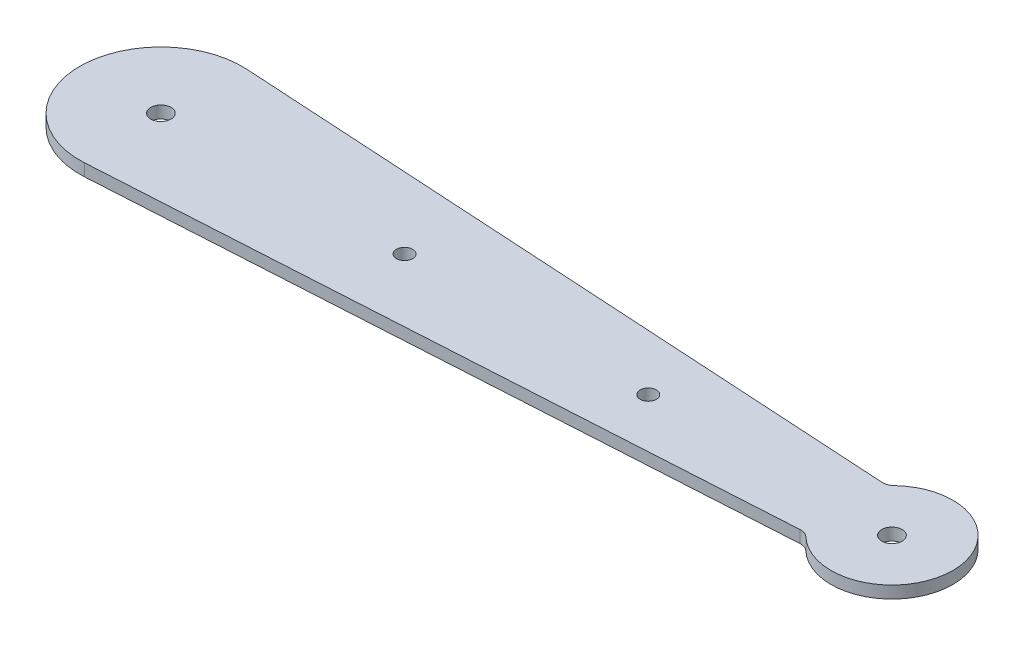
SolidWorks part; units mm, degrees
ref_plane "Front Plane" through (0, 0, 0) normal (0, 0, 1) x (1, 0, 0)
ref_plane "Top Plane" through (0, 0, 0) normal (0, 1, 0) x (1, 0, 0)
ref_plane "Right Plane" through (0, 0, 0) normal (1, 0, 0) x (0, 0, -1)
sketch "Sketch1" plane through (0, 0, 0) normal (0, 1, 0) x (1, 0, 0)
  line L0 (0, 0) -> (180, 0) construction
  line L1 (168.8197, 10) -> (1.1868, 19.9648)
  line L2 (168.8197, -10) -> (1.1868, -19.9648)
  circle A0 centre (0, 0) radius 20
  circle A1 centre (180, 0) radius 15
  circle A2 centre (0, 0) radius 2.5
  circle A3 centre (180, 0) radius 2.5
  circle A4 centre (60, 0) radius 2
  circle A5 centre (120, 0) radius 2
  dimension "D1" = 40
  dimension "D2" = 30
  dimension "D6" = 60
  dimension "D8" = 5
  dimension "D9" = 4
  dimension "D10" = 4
  dimension "D11" = 5
  dimension "D3" = 180
  dimension "D4" = 10
  dimension "D5" = 10
  dimension "D7" = 120
extrude "Boss-Extrude1" add sketch "Sketch1" along normal blind 3
fillet "Fillet2" radius 3 1 edges at (168.8197, 1.5, -10)
fillet "Fillet3" radius 3 1 edges at (168.8197, 1.5, 10)
